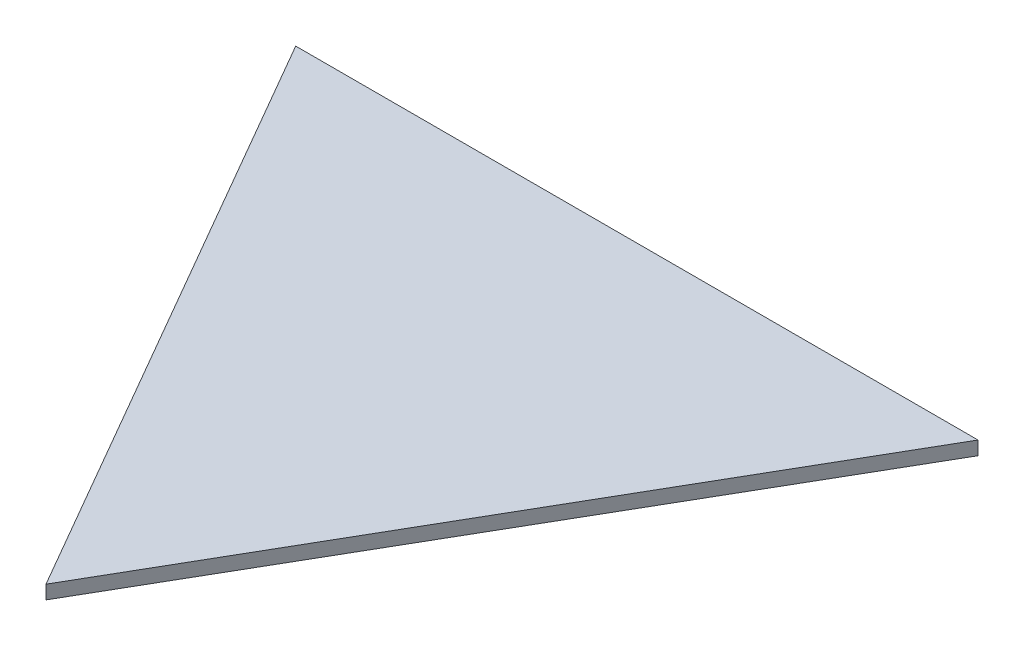
SolidWorks part; units mm, degrees
ref_plane "Front Plane" through (0, 0, 0) normal (0, 0, 1) x (1, 0, 0)
ref_plane "Top Plane" through (0, 0, 0) normal (0, 1, 0) x (1, 0, 0)
ref_plane "Right Plane" through (0, 0, 0) normal (1, 0, 0) x (0, 0, -1)
sketch "Sketch1" plane through (0, 0, 0) normal (0, 1, 0) x (1, 0, 0)
  line L0 (-250, 144.33) -> (0, -288.67)
  line L1 (-250, 144.33) -> (250, 144.33)
  line L2 (-250, 144.33) -> (-250, -288.67)
  line L3 (-250, -288.67) -> (250, -288.67)
  line L4 (250, 144.33) -> (250, -288.67)
  line L5 (0, -288.67) -> (250, 144.33)
  dimension "D1" = 433
  dimension "D2" = 500
  dimension "D3" = 250
  dimension "D4" = 144.33
  dimension "D5" = 250
extrude "Extrude1" add sketch "Sketch1" along normal blind 10 contours L0 L5 L1
